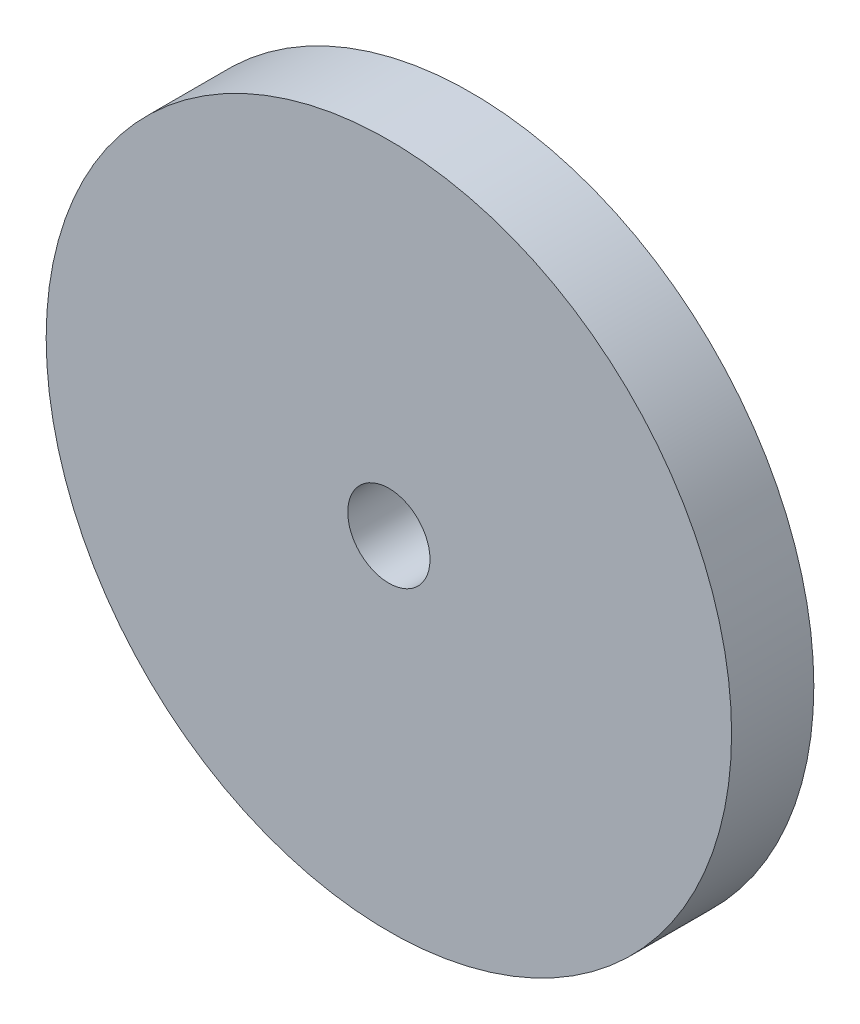
SolidWorks part; units mm, degrees
ref_plane "Front Plane" through (0, 0, 0) normal (0, 0, 1) x (1, 0, 0)
ref_plane "Top Plane" through (0, 0, 0) normal (0, 1, 0) x (1, 0, 0)
ref_plane "Right Plane" through (0, 0, 0) normal (1, 0, 0) x (0, 0, -1)
sketch "Sketch1" plane through (0, 0, 0) normal (0, 0, 1) x (1, 0, 0)
  circle A0 centre (0, 0) radius 12.5
  circle A1 centre (0, 0) radius 1.5
  dimension "D1" = 3
  dimension "D2" = 25
extrude "Boss-Extrude1" add sketch "Sketch1" along normal blind 3
